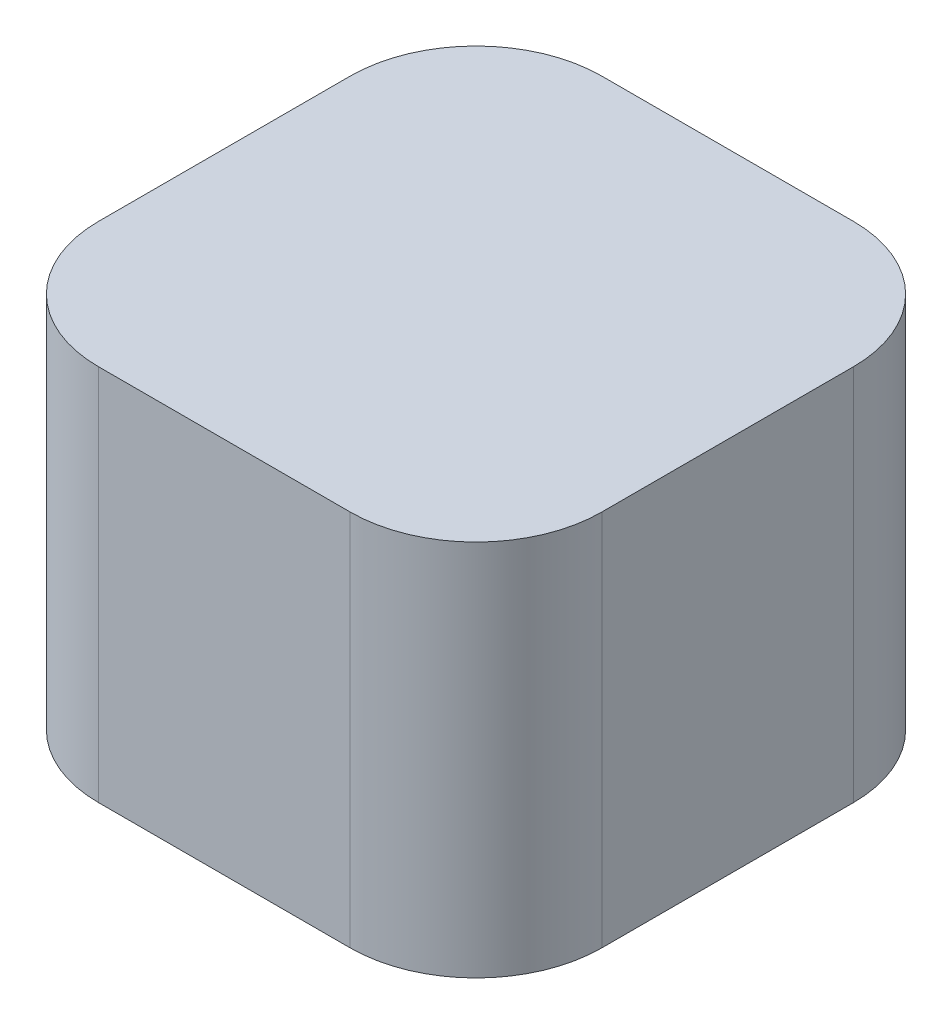
SolidWorks part; units mm, degrees
ref_plane "Front Plane" through (0, 0, 0) normal (0, 0, 1) x (1, 0, 0)
ref_plane "Top Plane" through (0, 0, 0) normal (0, 1, 0) x (1, 0, 0)
ref_plane "Right Plane" through (0, 0, 0) normal (1, 0, 0) x (0, 0, -1)
sketch "Sketch1" plane through (0, 0, 0) normal (0, 1, 0) x (1, 0, 0)
  line L1 (10, 0) -> (30, 0)
  line L2 (0, 10) -> (0, 30)
  line L3 (10, 40) -> (30, 40)
  line L4 (40, 10) -> (40, 30)
  arc A0 (10, 0) -> (0, 10) centre (10, 10) cw
  arc A1 (30, 0) -> (40, 10) centre (30, 10) ccw
  arc A2 (30, 40) -> (40, 30) centre (30, 30) cw
  arc A3 (0, 30) -> (10, 40) centre (10, 30) cw
  point P7 (0, 0)
  point P10 (40, 0)
  point P13 (40, 40)
  point P16 (0, 40)
  dimension "D3" = 10
  dimension "D1" = 40
  dimension "D2" = 40
extrude "Boss-Extrude1" add sketch "Sketch1" along normal blind 30
